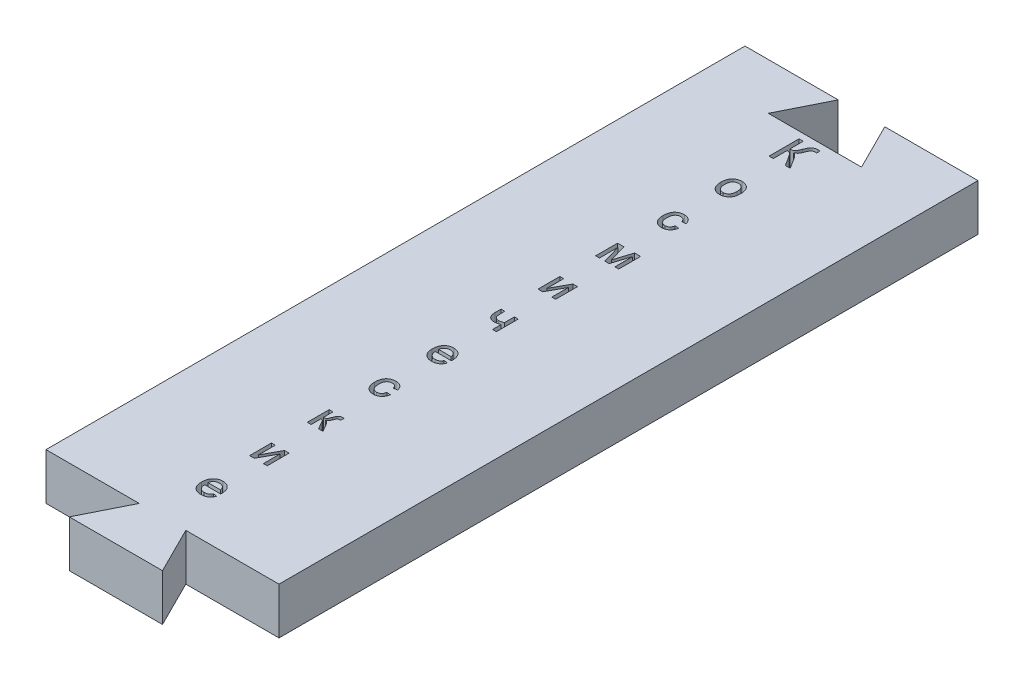
SolidWorks part; units mm, degrees
ref_plane "Спереди" through (0, 0, 0) normal (0, 0, 1) x (1, 0, 0)
ref_plane "Сверху" through (0, 0, 0) normal (0, 1, 0) x (1, 0, 0)
ref_plane "Справа" through (0, 0, 0) normal (1, 0, 0) x (0, 0, -1)
sketch "Эскиз1" plane through (0, 0, 0) normal (0, 1, 0) x (1, 0, 0)
  line L0 (10, 42.5) -> (2, 42.5)
  line L1 (10, -17.5) -> (2, -17.5)
  line L2 (10, -17.5) -> (10, 42.5)
  line L3 (-4, 38.5) -> (4, 38.5)
  line L4 (-10, -17.5) -> (-10, 42.5)
  line L5 (-4, -21.5) -> (4, -21.5)
  line L6 (4, -21.5) -> (2, -17.5)
  line L7 (-4, -21.5) -> (-2, -17.5)
  line L8 (-2, -17.5) -> (-10, -17.5)
  line L9 (4, 38.5) -> (2, 42.5)
  line L10 (-4, 38.5) -> (-2, 42.5)
  line L11 (-2, 42.5) -> (-10, 42.5)
  point P6 (-10, 42.5)
  dimension "D2" = 20
  dimension "D3" = 60
  dimension "D4" = 8
  dimension "D6" = 4
extrude "Бобышка-Вытянуть1" add sketch "Эскиз1" along normal blind 4 contours L4 L11 L10 L3 L9 L0 L2 L1 L6 L5 L7 L8
sketch "Эскиз2" plane through (0, 0, 0) normal (0, 1, 0) x (1, 0, 0)
  text T0 "К\r\nо\r\nс\r\nм\r\nи\r\nч\r\nе\r\nс\r\nк\r\nи\r\nе" font "Arial" height in points 10
  point P1 (0, 0)
  point P2 (-2.4824, 32.8577)
  point P3 (0, 0)
  point P4 (-1.4116, 35.6337)
  point P5 (0, 0)
  point P6 (0, 0)
  point P7 (0, 0)
  point P8 (-1.0484, 35.3541)
extrude "Вырез-Вытянуть1" cut sketch "Эскиз2" along normal through all
